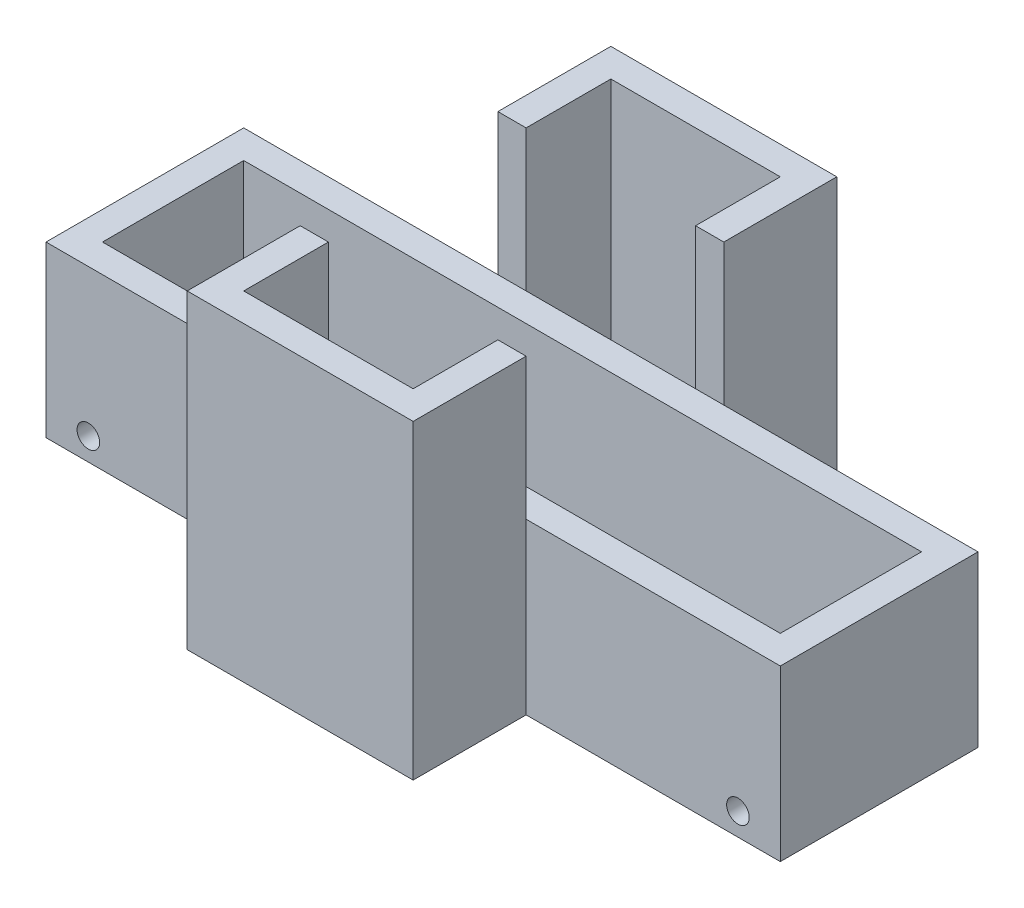
SolidWorks part; units mm, degrees
ref_plane "Front Plane" through (0, 0, 0) normal (0, 0, 1) x (1, 0, 0)
ref_plane "Top Plane" through (0, 0, 0) normal (0, 1, 0) x (1, 0, 0)
ref_plane "Right Plane" through (0, 0, 0) normal (1, 0, 0) x (0, 0, -1)
sketch "Sketch1" plane through (0, 0, 0) normal (0, 1, 0) x (1, 0, 0)
  line L1 (-65, 17.5) -> (65, 17.5)
  line L2 (-65, 17.5) -> (-65, -17.5)
  line L3 (-65, -17.5) -> (65, -17.5)
  line L4 (65, 17.5) -> (65, -17.5)
  line L5 (-65, 17.5) -> (65, -17.5) construction
  line L6 (-65, -17.5) -> (65, 17.5) construction
  point P0 (0, 0)
  dimension "D1" = 130
  dimension "D2" = 35
extrude "Boss-Extrude1" add sketch "Sketch1" along normal blind 30
sketch "Sketch2" plane through (0, 30, 0) normal (0, 1, 0) x (1, 0, 0)
  line L1 (-60, 12.5) -> (60, 12.5)
  line L2 (-60, 12.5) -> (-60, -12.5)
  line L3 (-60, -12.5) -> (60, -12.5)
  line L4 (60, 12.5) -> (60, -12.5)
  line L5 (-60, 12.5) -> (60, -12.5) construction
  line L6 (-60, -12.5) -> (60, 12.5) construction
  point P0 (0, 0)
  dimension "D1" = 120
  dimension "D2" = 25
extrude "Cut-Extrude1" cut sketch "Sketch2" against normal blind 25
sketch "Sketch3" plane through (0, 0, 17.5) normal (0, 0, 1) x (1, 0, 0)
  line L0 (65, 30) -> (65, 0) construction
  line L1 (-65, 0) -> (65, 0) construction
  line L2 (-65, 30) -> (-65, 0) construction
  circle A0 centre (57.5, 4) radius 2
  circle A1 centre (-57.5, 4) radius 2
  dimension "D5" = 4
  dimension "D6" = 4
  dimension "D1" = 7.5
  dimension "D2" = 4
  dimension "D3" = 7.5
  dimension "D4" = 4
extrude "Cut-Extrude2" cut sketch "Sketch3" against normal through all contours A1
sketch "Sketch4" plane through (0, 0, -17.5) normal (0, 0, -1) x (-1, 0, 0)
  line L0 (-65, 0) -> (65, 0) construction
  line L1 (-65, 30) -> (-65, 0) construction
  circle A0 centre (-57.5, 4) radius 2
  dimension "D3" = 4
  dimension "D1" = 4
  dimension "D2" = 7.5
extrude "Cut-Extrude3" cut sketch "Sketch4" against normal through all
sketch "Sketch6" plane through (0, 0, -17.5) normal (0, 0, -1) x (-1, 0, 0)
  line L0 (-65, 0) -> (65, 0) construction
  line L1 (-20, 0) -> (20, 0)
  line L2 (-20, 0) -> (-20, 55)
  line L3 (-20, 55) -> (20, 55)
  line L4 (20, 0) -> (20, 55)
  line L5 (65, 30) -> (65, 0) construction
  dimension "D1" = 40
  dimension "D2" = 45
  dimension "D3" = 55
extrude "Boss-Extrude2" add sketch "Sketch6" along normal blind 20
sketch "Sketch7" plane through (0, 55, 0) normal (0, 1, 0) x (1, 0, 0)
  line L0 (-20, 17.5) -> (20, 17.5) construction
  line L1 (-15, 17.5) -> (15, 17.5)
  line L2 (-15, 17.5) -> (-15, 32.5)
  line L3 (-15, 32.5) -> (15, 32.5)
  line L4 (15, 17.5) -> (15, 32.5)
  line L5 (20, 37.5) -> (20, 17.5) construction
  dimension "D1" = 15
  dimension "D2" = 30
  dimension "D3" = 5
extrude "Cut-Extrude4" cut sketch "Sketch7" against normal blind 50
sketch "Sketch8" plane through (0, 0, 17.5) normal (0, 0, 1) x (1, 0, 0)
  line L0 (-65, 0) -> (65, 0) construction
  line L1 (-20, 0) -> (20, 0)
  line L2 (-20, 0) -> (-20, 55)
  line L3 (-20, 55) -> (20, 55)
  line L4 (20, 0) -> (20, 55)
  dimension "D1" = 40
extrude "Boss-Extrude3" add sketch "Sketch8" along normal blind 20
sketch "Sketch9" plane through (0, 55, 0) normal (0, 1, 0) x (1, 0, 0)
  line L0 (20, -17.5) -> (-20, -17.5) construction
  line L1 (-15, -17.5) -> (15, -17.5)
  line L2 (-15, -17.5) -> (-15, -32.5)
  line L3 (-15, -32.5) -> (15, -32.5)
  line L4 (15, -17.5) -> (15, -32.5)
  line L5 (-20, -37.5) -> (-20, -17.5) construction
  dimension "D1" = 30
  dimension "D2" = 15
  dimension "D3" = 5
extrude "Cut-Extrude5" cut sketch "Sketch9" against normal blind 50
